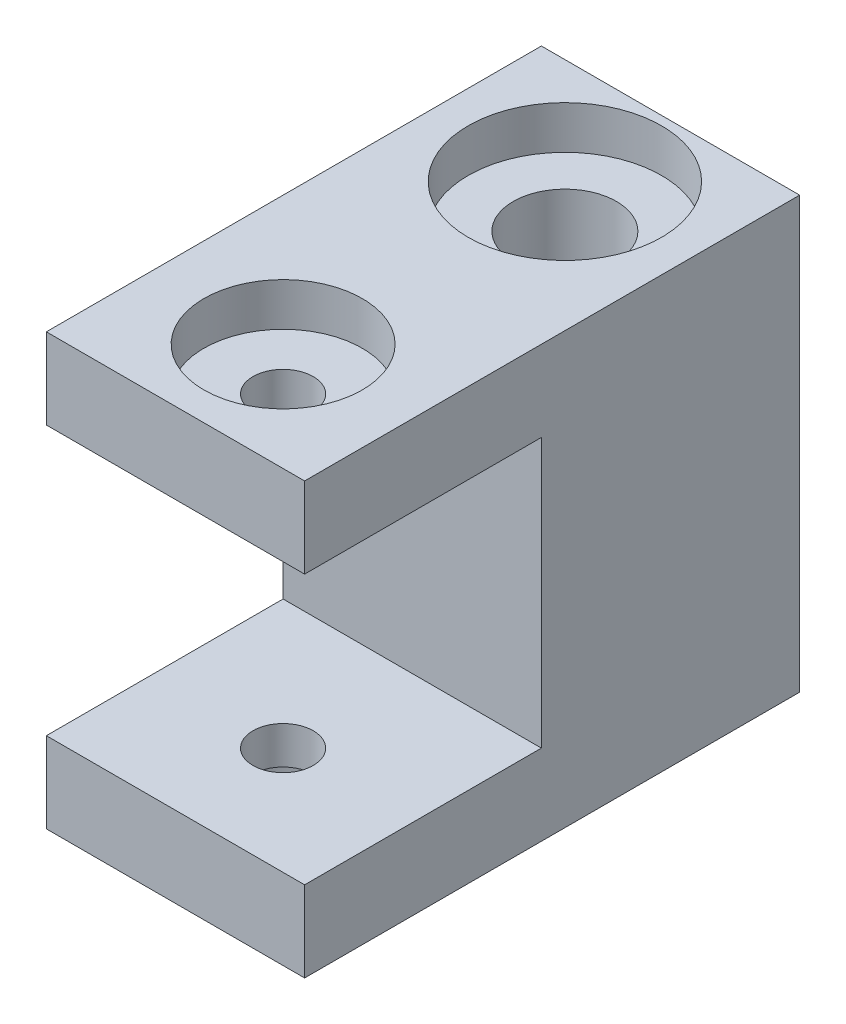
SolidWorks part; units mm, degrees
material "Delrin 2700 NC010, Low Viscosity Acetal Copolymer (SS)"
ref_plane "Front Plane" through (0, 0, 0) normal (0, 0, 1) x (1, 0, 0)
ref_plane "Top Plane" through (0, 0, 0) normal (0, 1, 0) x (1, 0, 0)
ref_plane "Right Plane" through (0, 0, 0) normal (1, 0, 0) x (0, 0, -1)
sketch "Sketch1" plane through (0, 0, 0) normal (0, 0, 1) x (1, 0, 0)
  line L1 (-19.05, -31.75) -> (19.05, -31.75)
  line L2 (-19.05, -31.75) -> (-19.05, 31.75)
  line L3 (-19.05, 31.75) -> (19.05, 31.75)
  line L4 (19.05, -31.75) -> (19.05, 31.75)
  line L5 (-19.05, -31.75) -> (19.05, 31.75) construction
  line L6 (-19.05, 31.75) -> (19.05, -31.75) construction
  point P0 (0, 0)
  dimension "D1" = 38.1
  dimension "D2" = 63.5
extrude "Boss-Extrude1" add sketch "Sketch1" along normal mid plane 73.025
sketch "Sketch2" plane through (19.05, 0, 0) normal (1, 0, 0) x (0, 0, -1)
  line L0 (-36.5125, -31.75) -> (-36.5125, 31.75) construction
  line L1 (-1.5875, -19.8438) -> (-36.5125, -19.8438)
  line L2 (-1.5875, -19.8438) -> (-1.5875, 19.8437)
  line L3 (-1.5875, 19.8437) -> (-36.5125, 19.8437)
  line L4 (-36.5125, -19.8438) -> (-36.5125, 19.8437)
  line L5 (-1.5875, -19.8438) -> (-36.5125, 19.8437) construction
  line L6 (-1.5875, 19.8437) -> (-36.5125, -19.8438) construction
  point P0 (-19.05, 0)
  dimension "D1" = 34.925
  dimension "D2" = 39.6875
extrude "Cut-Extrude1" cut sketch "Sketch2" against normal through all
sketch "Sketch3" plane through (0, 31.75, 0) normal (0, 1, 0) x (1, 0, 0)
  line L0 (-19.05, -20.6375) -> (19.05, -20.6375) construction
  line L1 (-19.05, -36.5125) -> (-19.05, 36.5125) construction
  line L2 (19.05, -36.5125) -> (19.05, 36.5125) construction
  circle A0 centre (0, -20.6375) radius 4.445
  dimension "D1" = 8.89
  dimension "D2" = 19.05
extrude "Cut-Extrude2" cut sketch "Sketch3" against normal through all
sketch "Sketch4" plane through (0, 31.75, 0) normal (0, 1, 0) x (1, 0, 0)
  circle A0 centre (0, -20.6375) radius 11.684
  dimension "D1" = 23.368
extrude "Cut-Extrude3" cut sketch "Sketch4" against normal blind 6.35
sketch "Sketch6" plane through (0, 31.75, 0) normal (0, 1, 0) x (1, 0, 0)
  line L2 (19.05, 36.5125) -> (-19.05, 36.5125) construction
  circle A0 centre (0, 20.9296) radius 14.2621
  point P4 (0, 6.6675)
  point P6 (0, 36.5125)
  dimension "D1" = 28.5242
  dimension "D2" = 29.845
extrude "Cut-Extrude5" cut sketch "Sketch6" against normal blind 6.35
mirror "Mirror1" about plane through (0, 0, 0) normal (0, 1, 0) of "Cut-Extrude5", "Cut-Extrude3"
sketch "Sketch7" plane through (0, 25.4, 0) normal (0, 1, 0) x (1, 0, 0)
  circle A0 centre (0, 20.9296) radius 7.62
  dimension "D1" = 15.24
extrude "Cut-Extrude6" cut sketch "Sketch7" against normal through all
